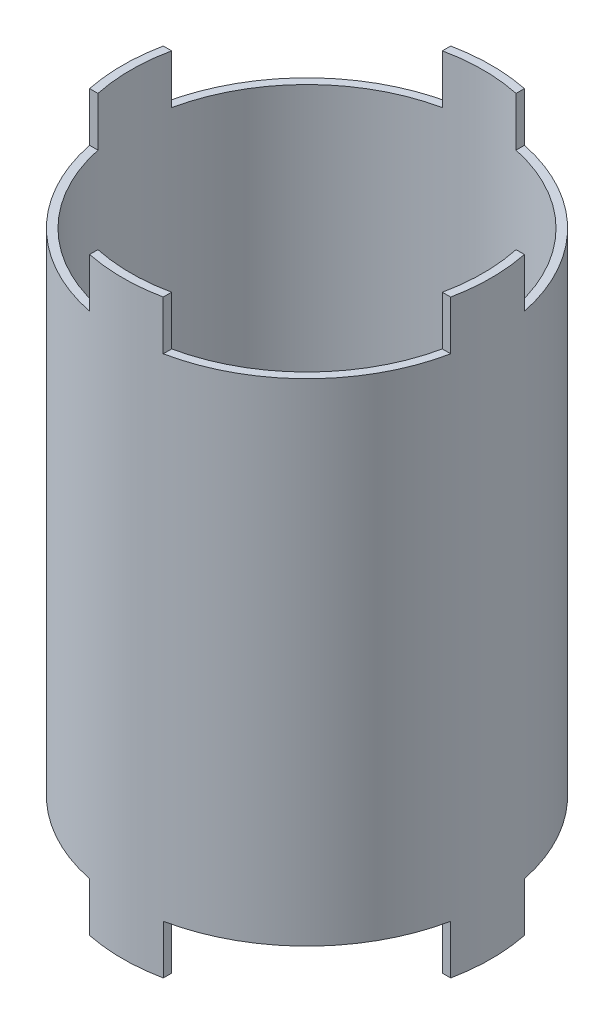
SolidWorks part; units mm, degrees
ref_plane "Front Plane" through (0, 0, 0) normal (0, 0, 1) x (1, 0, 0)
ref_plane "Top Plane" through (0, 0, 0) normal (0, 1, 0) x (1, 0, 0)
ref_plane "Right Plane" through (0, 0, 0) normal (1, 0, 0) x (0, 0, -1)
sketch "Sketch1" plane through (0, 0, 0) normal (0, 1, 0) x (1, 0, 0)
  circle A0 centre (0, 0) radius 57.15
  circle A1 centre (0, 0) radius 54.61
  dimension "D1" = 114.3
  dimension "D2" = 2.54
extrude "Boss-Extrude1" add sketch "Sketch1" along normal blind 152.4
sketch "Sketch2" plane through (0, 152.4, 0) normal (0, 1, 0) x (1, 0, 0)
  line L0 (-55.9953, 11.43) -> (-53.4004, 11.43)
  line L1 (-53.4004, -11.43) -> (-55.9953, -11.43)
  line L2 (11.43, 53.4004) -> (11.43, 55.9953)
  line L3 (-11.43, 53.4004) -> (-11.43, 55.9953)
  line L4 (53.4004, 11.43) -> (55.9953, 11.43)
  line L5 (53.4004, -11.43) -> (55.9953, -11.43)
  line L6 (11.43, -53.4004) -> (11.43, -55.9953)
  line L7 (-11.43, -53.4004) -> (-11.43, -55.9953)
  line L8 (11.43, -53.4004) -> (11.4137, -55.9987)
  arc A0 (-55.9953, -11.43) -> (-55.9953, 11.43) centre (0, 0) cw
  arc A1 (-11.43, 53.4004) -> (11.43, 53.4004) centre (0, 0) cw
  circle A2 centre (0, 0) radius 57.15 construction
  arc A3 (-53.4004, 11.43) -> (-53.4004, -11.43) centre (0, 0) ccw
  circle A4 centre (0, 0) radius 54.61 construction
  arc A5 (-11.43, 55.9953) -> (11.43, 55.9953) centre (0, 0) cw
  arc A6 (53.4004, 11.43) -> (53.4004, -11.43) centre (0, 0) cw
  arc A7 (55.9953, 11.43) -> (55.9953, -11.43) centre (0, 0) cw
  arc A8 (-11.43, -53.4004) -> (11.43, -53.4004) centre (0, 0) ccw
  arc A9 (-11.43, -55.9953) -> (11.4137, -55.9987) centre (0, 0) ccw
  dimension "D1" = 11.43
  dimension "D9" = 11.43
  dimension "D2" = 22.86
  dimension "D3" = 11.43
  dimension "D4" = 22.86
  dimension "D5" = 11.43
  dimension "D6" = 22.86
  dimension "D7" = 11.43
  dimension "D8" = 22.86
  dimension "D10" = 22.86
  dimension "D11" = 11.43
  dimension "D12" = 22.86
  dimension "D13" = 11.43
  dimension "D14" = 22.86
  dimension "D15" = 11.43
  dimension "D16" = 22.86
extrude "Boss-Extrude2" add sketch "Sketch2" along normal blind 15.24 contours A3 L1 A0 L0 | A1 L2 A5 L3 | A7 L5 A6 L4 | L8 A9 L7 A8
sketch "Sketch3" plane through (0, 0, 0) normal (0, -1, 0) x (1, 0, 0)
  line L10 (11.43, 55.9953) -> (11.43, 53.4004)
  line L11 (-11.43, 53.4004) -> (-11.43, 55.9953)
  line L12 (53.4004, 11.43) -> (55.9953, 11.43)
  line L13 (53.4004, -11.43) -> (55.9953, -11.43)
  line L14 (-11.43, -53.4004) -> (-11.43, -55.9953)
  line L15 (11.43, -53.4004) -> (11.43, -55.9953)
  line L16 (-55.9953, 11.43) -> (-53.4004, 11.43)
  line L17 (-55.9953, -11.43) -> (-53.4004, -11.43)
  arc A10 (-53.4004, 11.43) -> (-53.4004, -11.43) centre (0, 0) ccw
  circle A11 centre (0, 0) radius 54.61 construction
  arc A12 (-55.9953, 11.43) -> (-55.9953, -11.43) centre (0, 0) ccw
  circle A13 centre (0, 0) radius 57.15 construction
  arc A14 (-11.43, -53.4004) -> (11.43, -53.4004) centre (0, 0) ccw
  arc A15 (11.43, -55.9953) -> (-11.43, -55.9953) centre (0, 0) cw
  arc A16 (53.4004, -11.43) -> (53.4004, 11.43) centre (0, 0) ccw
  arc A17 (55.9953, -11.43) -> (55.9953, 11.43) centre (0, 0) ccw
  arc A18 (-11.43, 53.4004) -> (11.43, 53.4004) centre (0, 0) cw
  arc A19 (-11.43, 55.9953) -> (11.43, 55.9953) centre (0, 0) cw
  dimension "D1" = 11.43
  dimension "D7" = 22.86
  dimension "D2" = 11.43
  dimension "D3" = 22.86
  dimension "D4" = 22.86
  dimension "D5" = 11.43
  dimension "D6" = 11.43
  dimension "D8" = 11.43
  dimension "D9" = 11.43
  dimension "D10" = 22.86
  dimension "D11" = 22.86
  dimension "D12" = 11.43
  dimension "D13" = 11.43
  dimension "D14" = 22.86
  dimension "D15" = 22.86
extrude "Boss-Extrude3" add sketch "Sketch3" along normal blind 15.24 contours A15 L14 A14 L15 | A12 L17 A10 L16 | A17 L12 A16 L13 | A19 L10 A18 L11
equation "\"MDF\"= .6"
equation "\"Foamcore\"= .1"
equation "\"GMaterial\"= \"MDF\""
equation "\"D1@Boss-Extrude2\"=\"GMaterial\""
equation "\"D1@Boss-Extrude3\"=\"GMaterial\""
